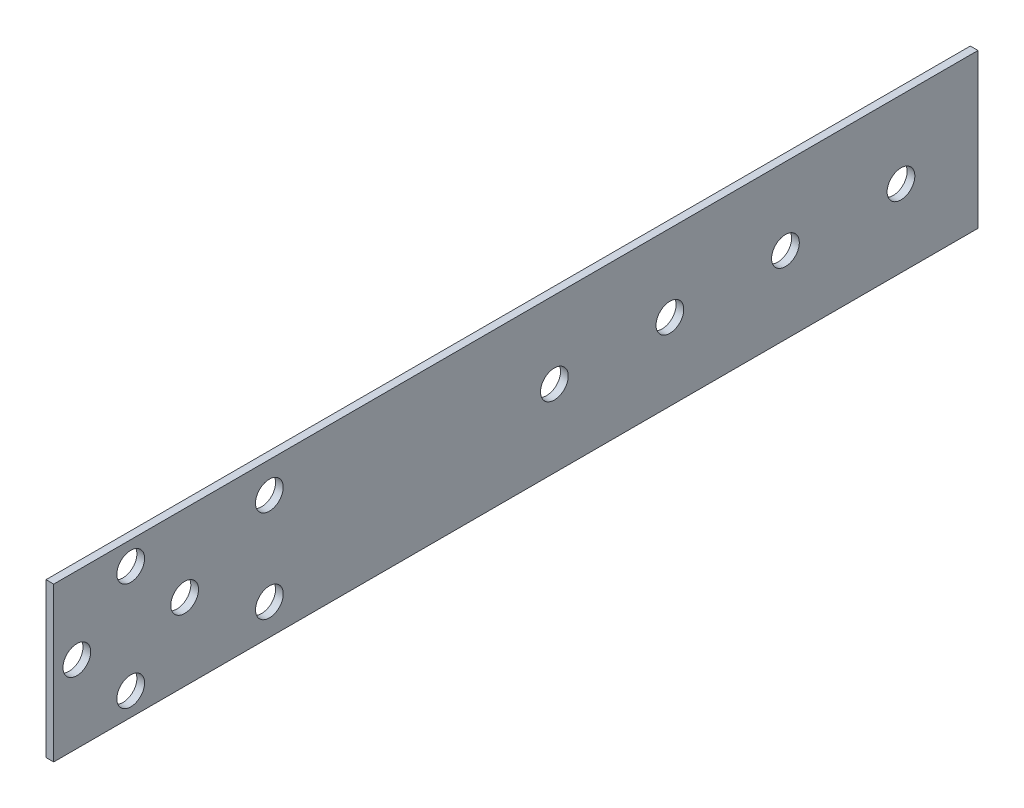
SolidWorks part; units mm, degrees
material "5052-O"
ref_plane "前视基准面" through (0, 0, 0) normal (0, 0, 1) x (1, 0, 0)
ref_plane "上视基准面" through (0, 0, 0) normal (0, 1, 0) x (1, 0, 0)
ref_plane "右视基准面" through (0, 0, 0) normal (1, 0, 0) x (0, 0, -1)
sketch "草图1" plane through (0, 0, 0) normal (0, 1, 0) x (1, 0, 0)
  line L14 (0, 0) -> (1, 0)
  line L16 (0, 0) -> (0, 120)
  line L17 (0, 120) -> (1, 120)
  line L18 (1, 0) -> (1, 120)
extrude "凸台-拉伸1" add sketch "草图1" along normal blind 20
sketch "草图2" plane through (0, 0, 0) normal (-1, 0, 0) x (0, 0, 1)
  circle A0 centre (-10, 10) radius 10
  circle A2 centre (-10, 17) radius 1.8
  circle A3 centre (-3, 10) radius 1.8
  circle A4 centre (-10, 3) radius 1.8
  circle A5 centre (-17, 10) radius 1.8
extrude "切除-拉伸1" cut sketch "草图2" against normal through all contours A2 | A5 | A3 | A4
sketch "草图3" plane through (0, 0, 0) normal (-1, 0, 0) x (0, 0, 1)
  line L0 (-120, 10) -> (-110, 10)
  line L1 (-120, 20) -> (-120, 0) construction
  line L2 (-110, 10) -> (-95, 10)
  line L3 (-95, 10) -> (-80, 10)
  line L4 (-80, 10) -> (-65, 10)
  circle A0 centre (-110, 10) radius 1.8
  circle A1 centre (-95, 10) radius 1.8
  circle A2 centre (-80, 10) radius 1.8
  circle A3 centre (-65, 10) radius 1.8
extrude "切除-拉伸3" cut sketch "草图3" against normal blind 10 contours A0 | A1 | A2 | A3
sketch "草图4" plane through (0, 0, 0) normal (-1, 0, 0) x (0, 0, 1)
  circle A0 centre (-28, 16) radius 1.8
  circle A1 centre (-28, 4) radius 1.8
extrude "切除-拉伸4" cut sketch "草图4" against normal through all
